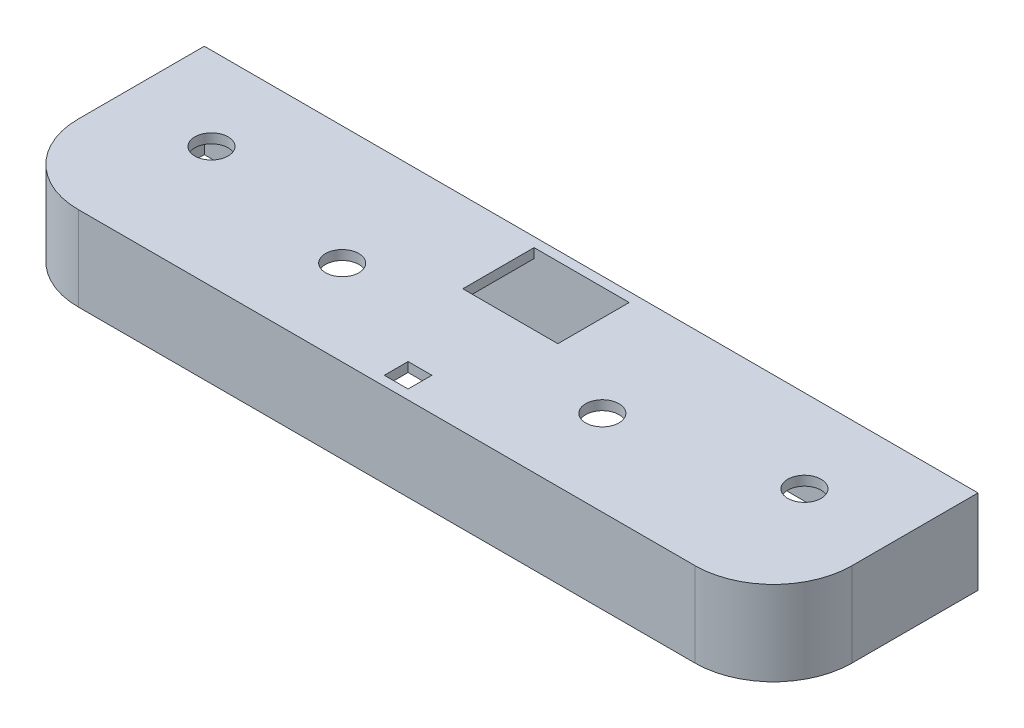
SolidWorks part; units mm, degrees
ref_plane "Front Plane" through (0, 0, 0) normal (0, 0, 1) x (1, 0, 0)
ref_plane "Top Plane" through (0, 0, 0) normal (0, 1, 0) x (1, 0, 0)
ref_plane "Right Plane" through (0, 0, 0) normal (1, 0, 0) x (0, 0, -1)
sketch "Sketch1" plane through (0, 0, 0) normal (0, 1, 0) x (1, 0, 0)
  line L1 (-81.35, -21.5) -> (81.35, -21.5)
  line L2 (-81.35, -21.5) -> (-81.35, 21.5)
  line L3 (-81.35, 21.5) -> (81.35, 21.5)
  line L4 (81.35, -21.5) -> (81.35, 21.5)
  line L5 (-81.35, -21.5) -> (81.35, 21.5) construction
  line L6 (-81.35, 21.5) -> (81.35, -21.5) construction
  point P0 (0, 0)
  dimension "D1" = 43
extrude "Boss-Extrude2" add sketch "Sketch1" along normal blind 17.75
fillet "Fillet2" radius 16.5 2 edges at (81.35, 8.875, 21.5) (-81.35, 8.875, 21.5)
shell "Shell1" thickness 2
sketch "Sketch2" plane through (0, 17.75, 0) normal (0, 1, 0) x (1, 0, 0)
  line L0 (-81.35, 21.5) -> (-81.35, -5) construction
  line L4 (-64.85, -21.5) -> (64.85, -21.5) construction
  line L5 (81.35, 21.5) -> (-81.35, 21.5) construction
  line L6 (0, 0) -> (0, -33.6312) construction
  circle A0 centre (-62.35, 4) radius 3.5
  circle A4 centre (-27.35, -3.5) radius 3.5
  circle A7 centre (27.35, -3.5) radius 3.5
  circle A8 centre (62.35, 4) radius 3.5
  dimension "D1" = 19
  dimension "D2" = 7
  dimension "D3" = 25.5
  dimension "D4" = 17.5
  dimension "D5" = 35
  dimension "D6" = 18
extrude "Cut-Extrude1" cut sketch "Sketch2" against normal through all
sketch "Sketch5" plane through (0, 17.75, 0) normal (0, 1, 0) x (1, 0, 0)
  line L0 (81.35, 21.5) -> (-81.35, 21.5) construction
  line L1 (-10, 19.5) -> (10, 19.5)
  line L2 (-10, 19.5) -> (-10, 4.5)
  line L3 (-10, 4.5) -> (10, 4.5)
  line L4 (10, 19.5) -> (10, 4.5)
  dimension "D1" = 2
  dimension "D2" = 20
  dimension "D3" = 10
  dimension "D4" = 15
extrude "Cut-Extrude2" cut sketch "Sketch5" against normal through all
sketch "Sketch6" plane through (0, 17.75, 0) normal (0, 1, 0) x (1, 0, 0)
  line L0 (-64.85, -21.5) -> (64.85, -21.5) construction
  line L1 (-2.5, -14.5) -> (2.5, -14.5)
  line L2 (-2.5, -14.5) -> (-2.5, -19.5)
  line L3 (-2.5, -19.5) -> (2.5, -19.5)
  line L4 (2.5, -14.5) -> (2.5, -19.5)
  dimension "D1" = 5
  dimension "D2" = 2
  dimension "D3" = 2.5
extrude "Cut-Extrude3" cut sketch "Sketch6" against normal through all
